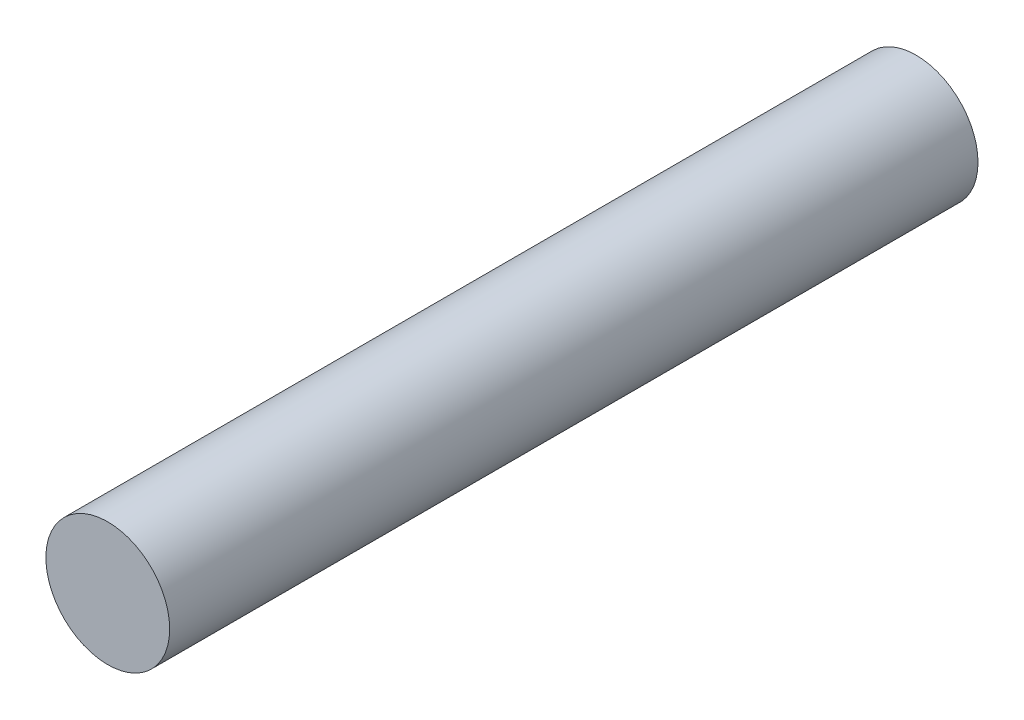
SolidWorks part; units mm, degrees
ref_plane "Front Plane" through (0, 0, 0) normal (0, 0, 1) x (1, 0, 0)
ref_plane "Top Plane" through (0, 0, 0) normal (0, 1, 0) x (1, 0, 0)
ref_plane "Right Plane" through (0, 0, 0) normal (1, 0, 0) x (0, 0, -1)
sketch "Sketch1" plane through (0, 0, 0) normal (0, 0, 1) x (1, 0, 0)
  circle A0 centre (0, 0) radius 10.72
extrude "Boss-Extrude1" add sketch "Sketch1" along normal blind 140
